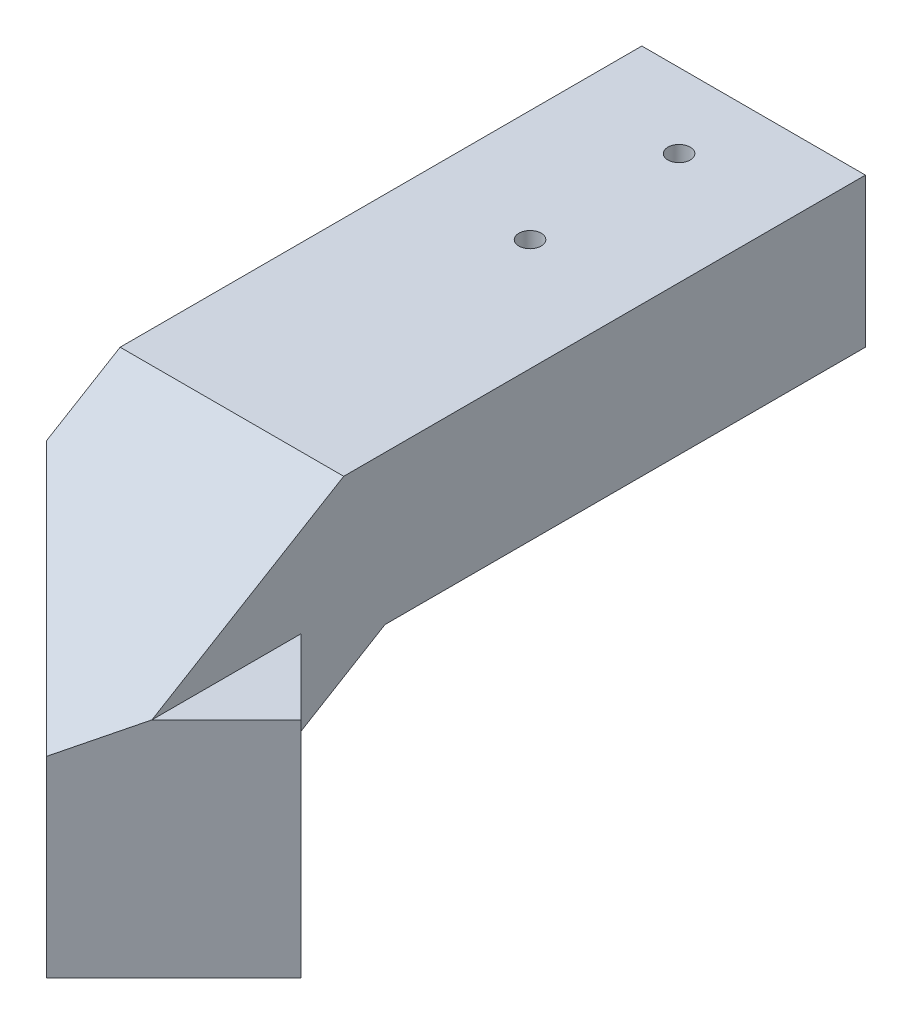
SolidWorks part; units mm, degrees
ref_plane "Alzado" through (0, 0, 0) normal (0, 0, 1) x (1, 0, 0)
ref_plane "Planta" through (0, 0, 0) normal (0, 1, 0) x (1, 0, 0)
ref_plane "Vista lateral" through (0, 0, 0) normal (1, 0, 0) x (0, 0, -1)
sketch "Croquis2" plane through (0, 0, 0) normal (1, 0, 0) x (0, 0, -1)
  line L0 (0, 0) -> (-50, 0)
  line L1 (-50, 0) -> (-75.7248, -15.4349)
  line L2 (-75.7248, -15.4349) -> (-75.7248, -45.4349)
  line L3 (0, -20) -> (-44.4603, -20)
  line L4 (-44.4603, -20) -> (-55.7248, -26.7587)
  line L5 (-55.7248, -26.7587) -> (-55.7248, -45.4349)
  line L6 (-75.7248, -45.4349) -> (-55.7248, -45.4349)
  line L7 (0, -20) -> (0, 0)
  dimension "D1" = 50
  dimension "D2" = 30
  dimension "D3" = 30
  dimension "D4" = 20
extrude "Saliente-Extruir2" add sketch "Croquis2" along normal blind 30
ref_plane "Plano1" through (-22.8624, 0, 22.8624) normal (-0.7071, 0, 0.7071) x (0.7071, 0, 0.7071)
sketch "Croquis3" plane through (-22.8624, 0, 22.8624) normal (-0.7071, 0, 0.7071) x (0.7071, 0, 0.7071)
  line L1 (81.8312, 10.6133) -> (21.2018, 10.6133)
  line L2 (81.8312, 10.6133) -> (81.8312, -50.3524)
  line L3 (81.8312, -50.3524) -> (21.2018, -50.3524)
  line L4 (21.2018, 10.6133) -> (21.2018, -50.3524)
extrude "Cortar-Extruir1" cut sketch "Croquis3" along normal blind 30
sketch "Croquis4" plane through (-22.8624, 0, 22.8624) normal (-0.7071, 0, 0.7071) x (0.7071, 0, 0.7071)
  circle A0 centre (60.6166, -34.2261) radius 3
  dimension "D1" = 6
extrude "Cortar-Extruir2" cut sketch "Croquis4" against normal through all
sketch "Croquis5" plane through (-22.8624, 0, 22.8624) normal (-0.7071, 0, 0.7071) x (0.7071, 0, 0.7071)
  line L1 (46.4744, -45.4349) -> (74.7587, -45.4349)
  line L2 (46.4744, -45.4349) -> (46.4744, -15.4349)
  line L3 (46.4744, -15.4349) -> (74.7587, -15.4349)
  line L4 (74.7587, -45.4349) -> (74.7587, -15.4349)
  line L5 (74.7587, -15.4349) -> (74.7587, -45.4349) construction
extrude "Saliente-Extruir3" add sketch "Croquis5" against normal up to vertex (14.1421 mm away)
sketch "Croquis6" plane through (-22.8624, 0, 22.8624) normal (-0.7071, 0, 0.7071) x (0.7071, 0, 0.7071)
  line L7 (32.3323, -20.7587) -> (46.4744, -26.7587)
  line L8 (46.4744, -26.7587) -> (46.4744, -45.4349)
  line L9 (46.4744, -45.4349) -> (74.7587, -45.4349)
  line L10 (74.7587, -45.4349) -> (74.7587, -15.4349)
  line L11 (74.7587, -15.4349) -> (38.3784, 0)
  line L12 (38.3784, 0) -> (32.3323, 0)
  line L13 (32.3323, 0) -> (32.3323, -20.7587)
  line L14 (32.3323, -20.7587) -> (46.4744, -26.7587)
  line L15 (46.4744, -26.7587) -> (46.4744, -45.4349)
  line L16 (46.4744, -45.4349) -> (74.7587, -45.4349)
  line L17 (74.7587, -45.4349) -> (74.7587, -15.4349)
  line L18 (74.7587, -15.4349) -> (38.3784, 0)
  line L19 (38.3784, 0) -> (32.3323, 0)
  line L20 (32.3323, 0) -> (32.3323, -20.7587)
  dimension "D1" = 0
extrude "Saliente-Extruir4" add sketch "Croquis6" along normal blind 10
sketch "Croquis7" plane through (0, 0, 0) normal (0, 1, 0) x (1, 0, 0)
  line L0 (0, 0) -> (0, -45.7248) construction
  line L1 (0, -42.9549) -> (-23.5817, -42.9549)
  line L2 (0, -42.9549) -> (0, -73.1611)
  line L3 (0, -73.1611) -> (-23.5817, -73.1611)
  line L4 (-23.5817, -42.9549) -> (-23.5817, -73.1611)
extrude "Cortar-Extruir3" cut sketch "Croquis7" against normal blind 60
sketch "Croquis8" plane through (-29.9335, 0, 29.9335) normal (-0.7071, 0, 0.7071) x (0.7071, 0, 0.7071)
  line L0 (60.6166, -45.4349) -> (60.6166, -35.4349) construction
  line L1 (46.4744, -45.4349) -> (74.7587, -45.4349) construction
  circle A0 centre (60.6166, -35.4349) radius 3
  dimension "D1" = 10
  dimension "D2" = 6
extrude "Cortar-Extruir4" cut sketch "Croquis8" against normal through all
ref_plane "Plano2" through (30, 0, 50) normal (-1, 0, 0) x (0, 0, 1)
sketch "Croquis10" plane through (0, 22.0588, 13.2353) normal (0, 0.8575, 0.5145) x (1, 0, 0)
  line L1 (47.0599, -40.39) -> (-32.0125, -40.39)
  line L2 (47.0599, -40.39) -> (47.0599, -96.7913)
  line L3 (47.0599, -96.7913) -> (-32.0125, -96.7913)
  line L4 (-32.0125, -40.39) -> (-32.0125, -96.7913)
extrude "Cortar-Extruir5" cut sketch "Croquis10" along normal blind 50
sketch "Croquis12" plane through (0, 0, 0) normal (0, 0, -1) x (-1, 0, 0)
  line L4 (0, -20) -> (0, 0)
  line L5 (0, 0) -> (-30, 0)
  line L6 (-30, 0) -> (-30, -20)
  line L7 (-30, -20) -> (0, -20)
  line L8 (0, -20) -> (0, 0)
  line L9 (0, 0) -> (-30, 0)
  line L10 (-30, 0) -> (-30, -20)
  line L11 (-30, -20) -> (0, -20)
  dimension "D1" = 0
extrude "Saliente-Extruir6" add sketch "Croquis12" along normal blind 20
sketch "Croquis13" plane through (0, -20, 0) normal (0, -1, 0) x (1, 0, 0)
  line L0 (15, -20) -> (15, 19.6739) construction
  line L1 (30, -20) -> (0, -20) construction
  circle A0 centre (15, -10) radius 1.5
  circle A1 centre (15, 10) radius 1.5
  dimension "D1" = 3
  dimension "D2" = 3
  dimension "D3" = 10
  dimension "D4" = 30
extrude "Cortar-Extruir6" cut sketch "Croquis13" against normal blind 20
move or copy body "Sólido-Mover/Copiar1" [suppressed] bodies to move or copy 113
ref_plane "Plano3" [suppressed] through (0, 0, 30) normal (0, 0, 1) x (1, 0, 0)
